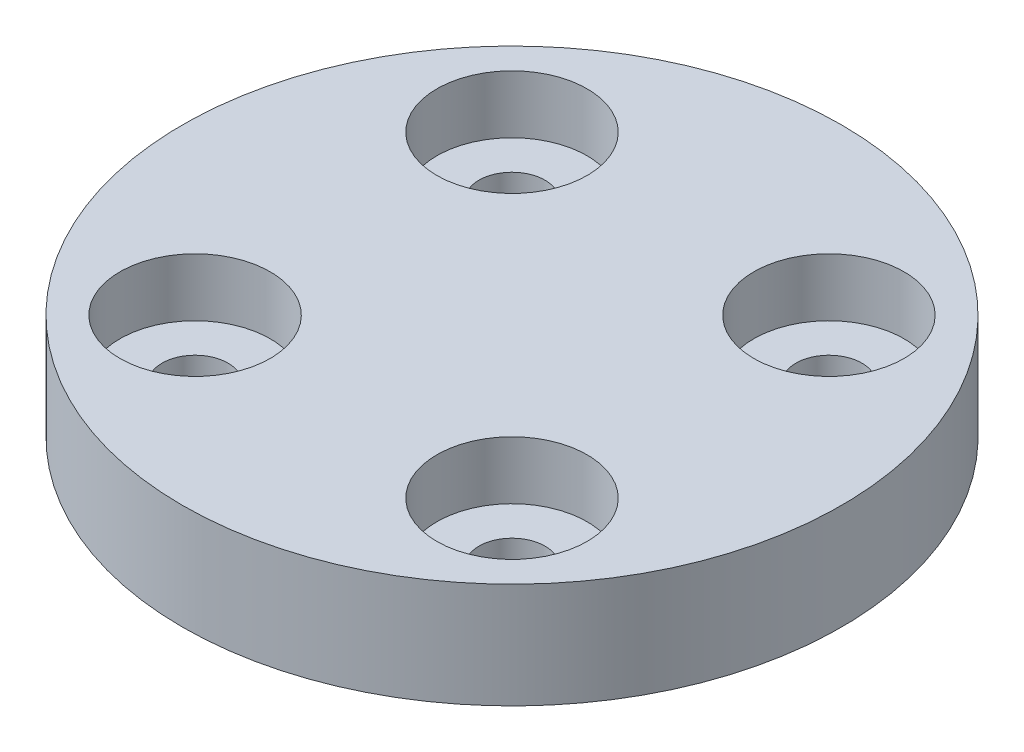
SolidWorks part; units mm, degrees
ref_plane "前视基准面" through (0, 0, 0) normal (0, 0, 1) x (1, 0, 0)
ref_plane "上视基准面" through (0, 0, 0) normal (0, 1, 0) x (1, 0, 0)
ref_plane "右视基准面" through (0, 0, 0) normal (1, 0, 0) x (0, 0, -1)
other "Configuration Table"
sketch "草图1" plane through (0, 0, 0) normal (0, 1, 0) x (1, 0, 0)
  circle A0 centre (0, 0) radius 12.5
  dimension "D1" = 25
extrude "凸台-拉伸1" add sketch "草图1" along normal blind 4
sketch "草图2" plane through (0, 4, 0) normal (0, 1, 0) x (1, 0, 0)
  line L0 (0, 12.5) -> (0, 0) construction
  line L1 (0, 0) -> (12.5, 0) construction
  line L2 (0, 0) -> (8.8388, 8.8388) construction
  circle A0 centre (0, 0) radius 12.5 construction
  circle A1 centre (6.0104, 6.0104) radius 2.85
  circle A2 centre (0, 0) radius 8.5 construction
  circle A3 centre (6.0104, -6.0104) radius 2.85
  circle A4 centre (-6.0104, -6.0104) radius 2.85
  circle A5 centre (-6.0104, 6.0104) radius 2.85
  point P20 (0, 0)
  dimension "D2" = 5.7
  dimension "D3" = 17
  dimension "D1" = 45
  dimension "D4" = 4
extrude "切除-拉伸1" cut sketch "草图2" against normal blind 2.2
sketch "草图3" plane through (0, 1.8, 0) normal (0, 1, 0) x (1, 0, 0)
  circle A0 centre (-6.0104, 6.0104) radius 1.25
  circle A1 centre (6.0104, 6.0104) radius 1.25
  circle A2 centre (6.0104, -6.0104) radius 1.25
  circle A3 centre (-6.0104, -6.0104) radius 1.25
  point P12 (0, 0)
  dimension "D1" = 2.5
  dimension "D2" = 4
extrude "切除-拉伸2" cut sketch "草图3" against normal blind 10
